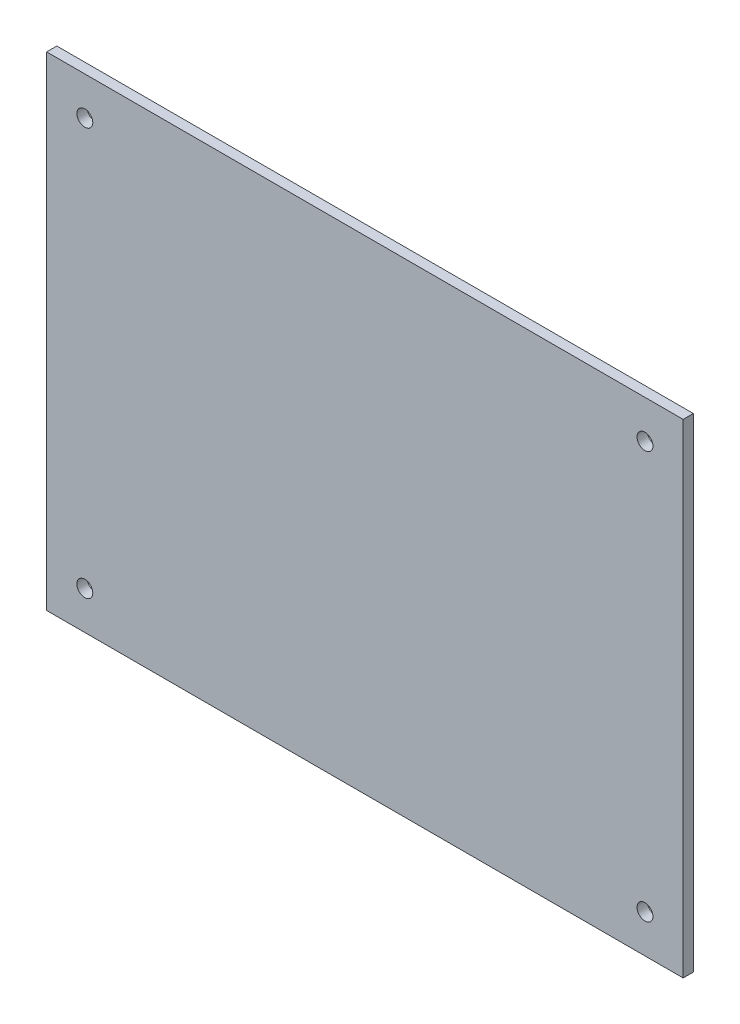
SolidWorks part; units mm, degrees
ref_plane "Front Plane" through (0, 0, 0) normal (0, 0, 1) x (1, 0, 0)
ref_plane "Top Plane" through (0, 0, 0) normal (0, 1, 0) x (1, 0, 0)
ref_plane "Right Plane" through (0, 0, 0) normal (1, 0, 0) x (0, 0, -1)
sketch "Sketch1" plane through (0, 0, 0) normal (0, 0, 1) x (1, 0, 0)
  line L1 (-50, -38) -> (50, -38)
  line L2 (-50, -38) -> (-50, 38)
  line L3 (-50, 38) -> (50, 38)
  line L4 (50, -38) -> (50, 38)
  line L5 (-50, -38) -> (50, 38) construction
  line L6 (-50, 38) -> (50, -38) construction
  circle A0 centre (-44, 32) radius 1.25
  circle A1 centre (44, 32) radius 1.25
  circle A2 centre (44, -32) radius 1.25
  circle A3 centre (-44, -32) radius 1.25
  point P0 (0, 0)
  point P14 (0, 0)
  point P15 (0, 0)
  point P16 (0, 0)
  point P17 (0, 0)
  dimension "D1" = 2.5
  dimension "D2" = 88
  dimension "D3" = 64
  dimension "D4" = 6
  dimension "D5" = 6
  dimension "D6" = 6
  dimension "D7" = 6
extrude "Boss-Extrude1" add sketch "Sketch1" along normal blind 1.6
